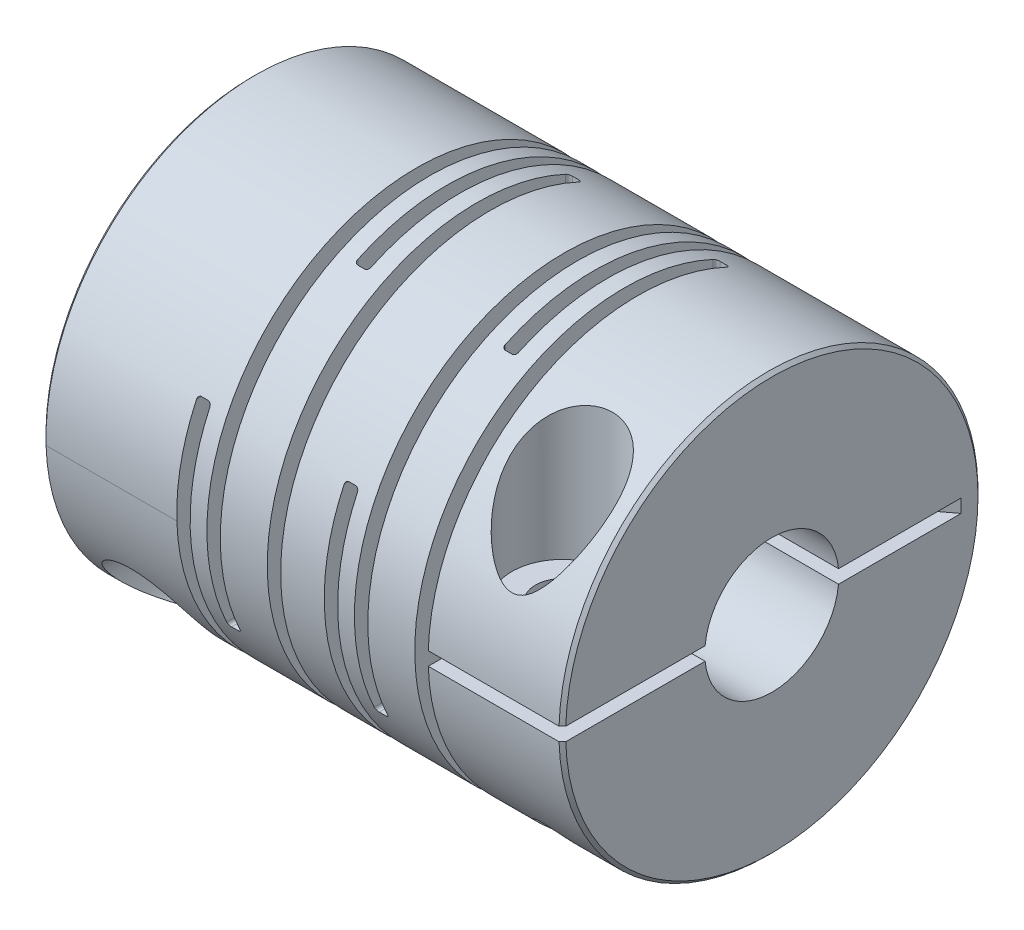
SolidWorks part; units mm, degrees
ref_plane "Front Plane" through (0, 0, 0) normal (0, 0, 1) x (1, 0, 0)
ref_plane "Top Plane" through (0, 0, 0) normal (0, 1, 0) x (1, 0, 0)
ref_plane "Right Plane" through (0, 0, 0) normal (1, 0, 0) x (0, 0, -1)
ref_plane "Plane1" through (0, 0, 12.5) normal (0, 0, 1) x (1, 0, 0)
ref_plane "Plane2" through (0, 12.5, 0) normal (0, 1, 0) x (1, 0, 0)
ref_plane "Plane3" through (31, 0, 0) normal (1, 0, 0) x (0, 0, -1)
sketch "Sketch1" plane through (0, 0, 0) normal (0, 0, 1) x (1, 0, 0)
  line L0 (0, 0) -> (31, 0) construction
  line L1 (0, 0) -> (31, 0)
  line L3 (0, 0) -> (0, 12.5)
  line L4 (0, 12.5) -> (31, 12.5)
  line L5 (31, 0) -> (31, 12.5)
  dimension "L" = 31
  dimension "D" = 25
revolve "Revolve1" add sketch "Sketch1" about L0
sketch "Sketch2" plane through (0, 0, 12.5) normal (0, 0, 1) x (1, 0, 0)
  line L0 (19.4, 12.5) -> (19.4, -5.3)
  line L1 (18.6, -5.3) -> (18.6, 12.5)
  line L2 (18.8, -5.5) -> (19.2, -5.5)
  line L3 (17.6, 5.3) -> (17.6, -12.5)
  line L4 (17.4, 5.5) -> (17, 5.5)
  line L5 (16.8, -12.5) -> (16.8, 5.3)
  line L6 (10.6, 12.5) -> (10.6, -5.3)
  line L7 (10, -5.5) -> (10.4, -5.5)
  line L8 (9.8, -5.3) -> (9.8, 12.5)
  line L9 (8.8, 5.3) -> (8.8, -12.5)
  line L10 (8.6, 5.5) -> (8.2, 5.5)
  line L11 (8, -12.5) -> (8, 5.3)
  line L12 (9.8, 12.5) -> (10.6, 12.5)
  line L13 (8, -12.5) -> (8.8, -12.5)
  line L14 (16.8, -12.5) -> (17.6, -12.5)
  line L15 (18.6, 12.5) -> (19.4, 12.5)
  line L16 (0, 0) -> (31, 0) construction
  line L17 (31, -8.8) -> (31, 8.8) construction
  arc A0 (19.2, -5.5) -> (19.4, -5.3) centre (19.2, -5.3) ccw
  arc A1 (18.6, -5.3) -> (18.8, -5.5) centre (18.8, -5.3) ccw
  arc A2 (17.6, 5.3) -> (17.4, 5.5) centre (17.4, 5.3) ccw
  arc A3 (17, 5.5) -> (16.8, 5.3) centre (17, 5.3) ccw
  arc A4 (10.4, -5.5) -> (10.6, -5.3) centre (10.4, -5.3) ccw
  arc A5 (9.8, -5.3) -> (10, -5.5) centre (10, -5.3) ccw
  arc A6 (8.8, 5.3) -> (8.6, 5.5) centre (8.6, 5.3) ccw
  arc A7 (8.2, 5.5) -> (8, 5.3) centre (8.2, 5.3) ccw
  dimension "FIX_3" = 0.2
  dimension "FIX_1" = 12.5
  dimension "D" = 25
  dimension "L_s" = 8
  dimension "MSM_1" = 5.3
  dimension "MSM_2" = 11.6
  dimension "MSM_4" = 0.8
extrude "Cut-Extrude1" cut sketch "Sketch2" against normal through all
sketch "Sketch3" plane through (0, 12.5, 0) normal (0, 1, 0) x (1, 0, 0)
  line L0 (21.2, 12.5) -> (21.2, -5.3)
  line L1 (20.4, -5.3) -> (20.4, 12.5)
  line L2 (20.6, -5.5) -> (21, -5.5)
  line L3 (23, 5.3) -> (23, -12.5)
  line L4 (22.8, 5.5) -> (22.4, 5.5)
  line L5 (22.2, -12.5) -> (22.2, 5.3)
  line L6 (12.4, 12.5) -> (12.4, -5.3)
  line L7 (11.8, -5.5) -> (12.2, -5.5)
  line L8 (11.6, -5.3) -> (11.6, 12.5)
  line L9 (14.2, 5.3) -> (14.2, -12.5)
  line L10 (14, 5.5) -> (13.6, 5.5)
  line L11 (13.4, -12.5) -> (13.4, 5.3)
  line L12 (11.6, 12.5) -> (12.4, 12.5)
  line L13 (13.4, -12.5) -> (14.2, -12.5)
  line L14 (22.2, -12.5) -> (23, -12.5)
  line L15 (20.4, 12.5) -> (21.2, 12.5)
  line L16 (0, 0) -> (31, 0) construction
  line L17 (31, -8.8) -> (31, 8.8) construction
  arc A0 (21, -5.5) -> (21.2, -5.3) centre (21, -5.3) ccw
  arc A1 (20.4, -5.3) -> (20.6, -5.5) centre (20.6, -5.3) ccw
  arc A2 (23, 5.3) -> (22.8, 5.5) centre (22.8, 5.3) ccw
  arc A3 (22.4, 5.5) -> (22.2, 5.3) centre (22.4, 5.3) ccw
  arc A4 (12.2, -5.5) -> (12.4, -5.3) centre (12.2, -5.3) ccw
  arc A5 (11.6, -5.3) -> (11.8, -5.5) centre (11.8, -5.3) ccw
  arc A6 (14.2, 5.3) -> (14, 5.5) centre (14, 5.3) ccw
  arc A7 (13.6, 5.5) -> (13.4, 5.3) centre (13.6, 5.3) ccw
  dimension "FIX_4" = 0.2
  dimension "FIX_1" = 12.5
  dimension "D" = 25
  dimension "L_s" = 8
  dimension "MSM_1" = 5.3
  dimension "MSM_2" = 11.6
  dimension "MSM_4" = 0.8
extrude "Cut-Extrude2" cut sketch "Sketch3" against normal through all
chamfer "Chamfer1" distance 0.2 2 edges at (31, 0, 12.5) (0, 0, 12.5)
sketch "Sketch4" plane through (0, 0, 0) normal (0, 0, 1) x (1, 0, 0)
  line L1 (0, 0) -> (25.1364, 0) construction
  line L2 (8.4, -12.5) -> (-11.6, -12.5)
  line L3 (-11.6, -12.5) -> (-11.6, 15)
  line L4 (8.4, -5) -> (8.4, -12.5)
  line L6 (-11.6, 15) -> (8.4, 15) construction
  line L7 (8.4, 15) -> (8.4, -12.5) construction
  arc A1 (8.4, -5) -> (-11.6, 15) centre (-11.6, -5) ccw
  dimension "FIX_1" = 12.5
  dimension "MSM_5" = 20
  dimension "MSM_6" = 8.4
  dimension "MSM_7" = 7.5
extrude "Cut-Extrude3" cut sketch "Sketch4" against normal mid plane 0.8
sketch "Sketch5" plane through (0, 0, 0) normal (0, 1, 0) x (1, 0, 0)
  line L0 (22.6, -12.5) -> (42.6, -12.5)
  line L1 (42.6, -12.5) -> (42.6, 15)
  line L2 (22.6, -5) -> (22.6, -12.5)
  line L3 (42.6, 15) -> (22.6, 15) construction
  line L4 (22.6, 15) -> (22.6, -12.5) construction
  line L5 (0, 0) -> (31, 0) construction
  line L6 (31, -8.8) -> (31, 8.8) construction
  arc A0 (42.6, 15) -> (22.6, -5) centre (42.6, -5) ccw
  dimension "FIX_1" = 12.5
  dimension "MSM_5" = 20
  dimension "MSM_6" = 8.4
  dimension "MSM_7" = 7.5
extrude "Cut-Extrude4" cut sketch "Sketch5" against normal mid plane 0.8
hole_wizard "Socket Head Cap Screw1" positions "Sketch8" profile "Sketch7" counterbore size "M2.5" standard "JIS"
sketch "Sketch8" plane through (0, 0, 12.5) normal (0, 0, 1) x (1, 0, 0)
  point P0 (4, -8.5)
  dimension "A" = 8.5
  dimension "F" = 4
sketch "Sketch7" plane through (4, -8.5, 12.5) normal (1, 0, 0) x (0, -1, 0)
  line L0 (0, 0) -> (0, 12.1)
  line L1 (0, 12.1) -> (1.6, 12.1)
  line L3 (1.6, 12.1) -> (1.6, 9.5)
  line L4 (1.6, 9.5) -> (3, 9.5)
  line L5 (3, 9.5) -> (3, 0)
  line L7 (3, 0) -> (0, 0)
  line L11 (0, 0) -> (0, 12.1) construction
  dimension "Thru Hole Depth" = 12.1
  dimension "MSM_8" = 6
  dimension "MSM_9" = 3.2
  dimension "MSM_10" = 9.5
hole_wizard "Tap1" positions "Sketch10" profile "Sketch9" hole size "M2x0.4" standard "JIS" end condition through all
sketch "Sketch10" plane through (0, 0, -0.4) normal (0, 0, 1) x (1, 0, 0)
  point P0 (4, -8.5)
  dimension "A" = 8.5
  dimension "F" = 4
sketch "Sketch9" plane through (4, -8.5, -0.4) normal (1, 0, 0) x (0, -1, 0)
  line L0 (0, 0) -> (0, 12.1)
  line L1 (0, 12.1) -> (1.2295, 12.1)
  line L2 (1.2295, 12.1) -> (1.2295, 0)
  line L5 (1.2295, 0) -> (0, 0)
  line L11 (0, 0) -> (0, 12.1) construction
  dimension "Thru Hole Depth" = 12.1
  dimension "STD" = 2.459
cosmetic thread "Thread1" parameters "M"=3
hole_wizard "Socket Head Cap Screw2" positions "Sketch12" profile "Sketch11" counterbore size "M2.5" standard "JIS"
sketch "Sketch12" plane through (0, 12.5, 0) normal (0, 1, 0) x (1, 0, 0)
  line L4 (31, -8.8) -> (31, 8.8) construction
  point P0 (27, -8.5)
  dimension "A" = 8.5
  dimension "F" = 4
sketch "Sketch11" plane through (27, 12.5, 8.5) normal (1, 0, 0) x (0, 0, 1)
  line L0 (0, 0) -> (0, 12.1)
  line L1 (0, 12.1) -> (1.6, 12.1)
  line L3 (1.6, 12.1) -> (1.6, 9.5)
  line L4 (1.6, 9.5) -> (3, 9.5)
  line L5 (3, 9.5) -> (3, 0)
  line L7 (3, 0) -> (0, 0)
  line L11 (0, 0) -> (0, 12.1) construction
  dimension "Thru Hole Depth" = 12.1
  dimension "MSM_8" = 6
  dimension "MSM_9" = 3.2
  dimension "MSM_10" = 9.5
hole_wizard "Tap2" positions "Sketch14" profile "Sketch13" hole size "M2x0.4" standard "JIS" end condition through all
sketch "Sketch14" plane through (0, -0.4, 0) normal (0, 1, 0) x (1, 0, 0)
  line L0 (31, -8.8) -> (31, 8.8) construction
  point P0 (27, -8.5)
  dimension "A" = 8.5
  dimension "F" = 4
sketch "Sketch13" plane through (27, -0.4, 8.5) normal (1, 0, 0) x (0, 0, 1)
  line L0 (0, 0) -> (0, 12.1)
  line L1 (0, 12.1) -> (1.2295, 12.1)
  line L2 (1.2295, 12.1) -> (1.2295, 0)
  line L5 (1.2295, 0) -> (0, 0)
  line L11 (0, 0) -> (0, 12.1) construction
  dimension "Thru Hole Depth" = 12.1
  dimension "STD" = 2.459
cosmetic thread "Thread2" parameters "M"=3
sketch "Sketch15" plane through (0, 0, 0) normal (0, 0, 1) x (1, 0, 0)
  line L0 (0, 0) -> (31, 0) construction
  line L1 (31, -8.8) -> (31, 8.8) construction
  line L2 (8, -12.5) -> (8, 5.3) construction
  line L3 (0, 0) -> (31, 0) construction
  line L4 (8, 0) -> (8, 4.25)
  line L5 (8, 4.25) -> (23, 4.25)
  line L6 (23, 0) -> (23, 4.25)
  line L7 (8, 0) -> (23, 0)
  dimension "FIX_9" = 8.5
revolve "Cut-Revolve1" cut sketch "Sketch15" about L0
sketch "Sketch16" plane through (0, 0, 0) normal (0, 0, 1) x (1, 0, 0)
  line L0 (0, 0.0033) -> (31, 0.0033) construction
  line L1 (0, 12.3) -> (0, -12.2935) construction
  line L2 (31, -8.8) -> (31, 8.8) construction
  line L3 (8, 0.0033) -> (8, 4.0033)
  line L4 (8, 4.0033) -> (23, 4.0033)
  line L5 (23, 4.0033) -> (23, 0.0033)
  line L6 (8, -12.5) -> (8, 5.3) construction
  line L7 (8, 0.0033) -> (23, 0.0033)
  dimension "D2_s" = 8
revolve "Cut-Revolve2" [suppressed] cut sketch "Sketch16" about L0
sketch "Sketch17" plane through (0, 0, 0) normal (1, 0, 0) x (0, 0, -1)
  circle A0 centre (0, 0) radius 4
  dimension "D1_s" = 8
extrude "Cut-Extrude5" cut sketch "Sketch17" along normal up to surface (8 mm away)
sketch "Sketch18" plane through (31, 0, 0) normal (1, 0, 0) x (0, 0, -1)
  circle A0 centre (0, 0) radius 4
  dimension "D2_s" = 8
extrude "Cut-Extrude6" cut sketch "Sketch18" against normal up to surface (8 mm away) up to face at (23, 0, 3.7185)
equation "\"FIX_1@Plane1\"= \"D@Sketch1\" / 2"
equation "\"FIX_9@Sketch15\"= \"D1_s@Sketch17\" + 0.5"
equation "\"Cut-Revolve1\" = if ( \"D1_s@Sketch17\" = \"D2_s@Sketch18\" , \"unsuppressed\" , \"suppressed\" )"
equation "\"Cut-Revolve2\" = if ( \"D1_s@Sketch17\" < > \"D2_s@Sketch18\" , \"unsuppressed\" , \"suppressed\" )"
